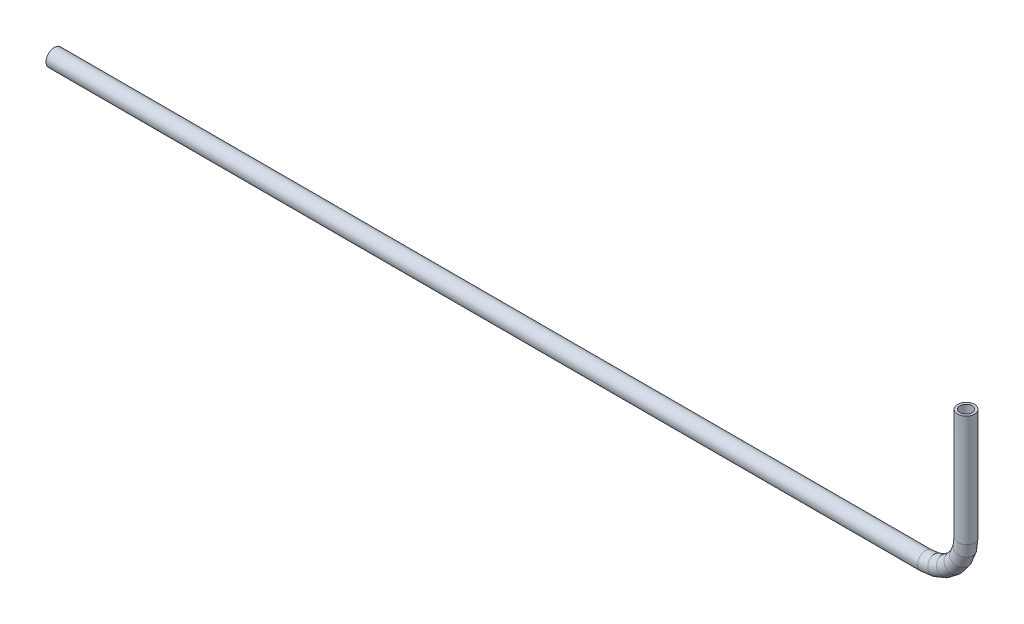
SolidWorks part; units mm, degrees
ref_plane "Front Plane" through (0, 0, 0) normal (0, 0, 1) x (1, 0, 0)
ref_plane "Top Plane" through (0, 0, 0) normal (0, 1, 0) x (1, 0, 0)
ref_plane "Right Plane" through (0, 0, 0) normal (1, 0, 0) x (0, 0, -1)
sketch3d "Path"
  line L0 (-3351.1428, -88, 0) -> (-3023.5928, -88, 0)
  line L1 (-3023.5928, -88, 0) -> (-3019.7105, -87.4889, 0)
  line L2 (-3019.7105, -87.4889, 0) -> (-3016.0928, -85.9904, 0)
  line L3 (-3016.0928, -85.9904, 0) -> (-3012.9862, -83.6066, 0)
  line L4 (-3012.9862, -83.6066, 0) -> (-3010.6024, -80.5, 0)
  line L5 (-3010.6024, -80.5, 0) -> (-3009.1039, -76.8823, 0)
  line L6 (-3009.1039, -76.8823, 0) -> (-3008.5928, -73, 0)
  line L7 (-3008.5928, -73, 0) -> (-3008.5928, -31.3, 0)
ref_plane "Start Plane" through (-3351.1428, 0, 0) normal (1, 0, 0) x (0, 0, -1)
sketch "Profile" plane through (-3351.1428, 0, 0) normal (1, 0, 0) x (0, 0, -1)
  circle A0 centre (0, -88) radius 3.175
  circle A1 centre (0, -88) radius 2.286
sweep "Tube" add profiles "Profile" path "Path"
